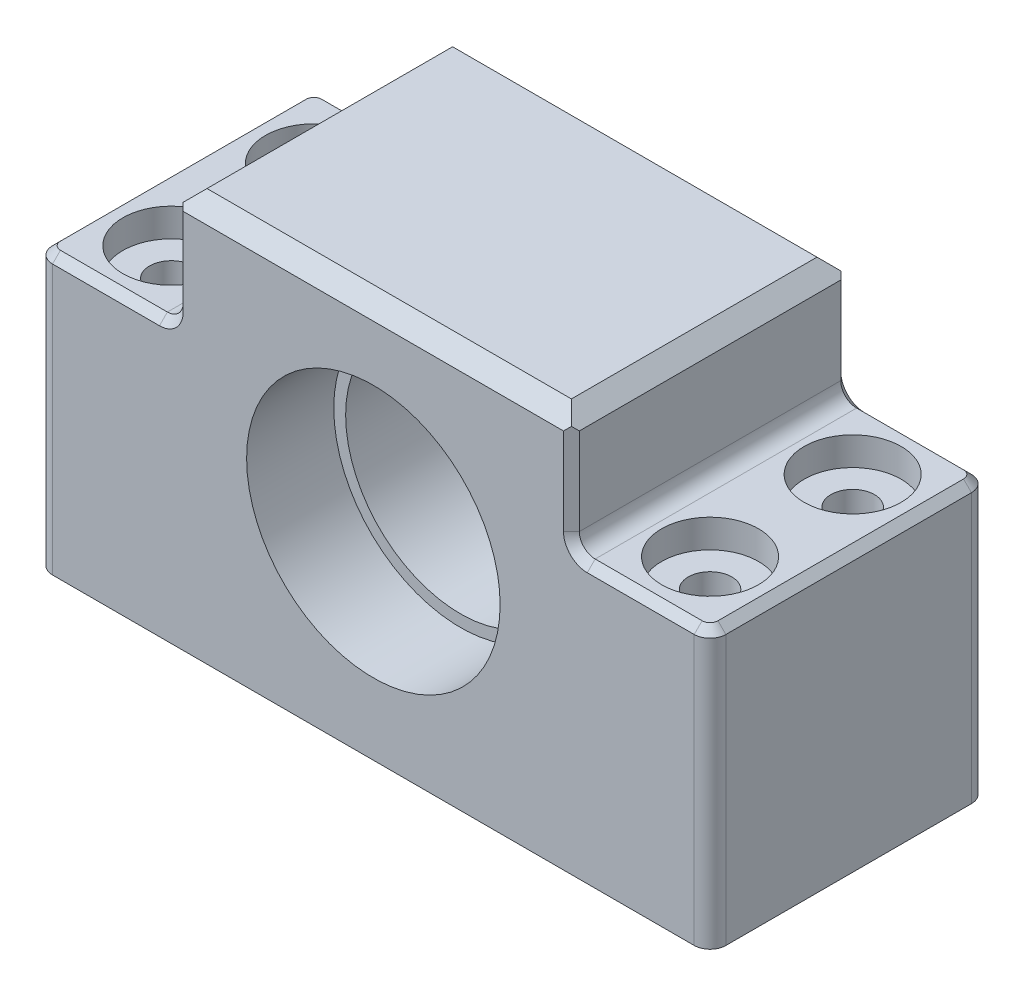
SolidWorks part; units mm, degrees
ref_plane "Front Plane" through (0, 0, 0) normal (0, 0, 1) x (1, 0, 0)
ref_plane "Top Plane" through (0, 0, 0) normal (0, 1, 0) x (1, 0, 0)
ref_plane "Right Plane" through (0, 0, 0) normal (1, 0, 0) x (0, 0, -1)
sketch "Sketch1" plane through (0, 0, 0) normal (0, 0, 1) x (1, 0, 0)
  line L0 (-25, -30) -> (-42.5, -30)
  line L1 (25, -30) -> (-25, -30)
  line L2 (25, -30) -> (25, 20) construction
  line L3 (25, 20) -> (-25, 20)
  line L4 (-25, -30) -> (-25, 20) construction
  line L5 (25, -30) -> (-25, 20) construction
  line L6 (25, 20) -> (-25, -30) construction
  line L7 (-42.5, -30) -> (-42.5, 5)
  line L8 (-42.5, 5) -> (-25, 5)
  line L9 (-25, 5) -> (-25, 20)
  line L10 (0, -55) -> (0, 55) construction
  line L11 (42.5, 5) -> (25, 5)
  line L12 (42.5, -30) -> (42.5, 5)
  line L13 (25, -30) -> (42.5, -30)
  line L14 (25, 5) -> (25, 20)
  circle A1 centre (0, -5) radius 16
  point P0 (0, -5)
  dimension "D1" = 25
  dimension "D3" = 32
  dimension "D2" = 50
  dimension "D4" = 85
  dimension "D5" = 35
  dimension "D6" = 50
extrude "Boss-Extrude1" add sketch "Sketch1" along normal mid plane 35
sketch "Sketch2" plane through (0, 0, 0) normal (0, 0, 1) x (1, 0, 0)
  circle A3 centre (0, -5) radius 16 construction
  circle A4 centre (0, -5) radius 16
  circle A5 centre (0, -5) radius 14.5
  dimension "D1" = 1.5
extrude "Boss-Extrude2" add sketch "Sketch2" along normal mid plane 13
sketch "Sketch3" plane through (0, 5, 0) normal (0, 1, 0) x (1, 0, 0)
  line L0 (34, 0) -> (-34, 0) construction
  line L1 (-34, -9) -> (-34, 9) construction
  line L4 (0, -55) -> (0, 55) construction
  line L5 (34, -9) -> (34, 9) construction
  circle A0 centre (-34, 9) radius 2.6
  circle A1 centre (-34, -9) radius 2.6
  circle A2 centre (34, 9) radius 2.6
  circle A3 centre (34, -9) radius 2.6
  point P8 (0, 0)
  dimension "D1" = 5.2
  dimension "D2" = 34
  dimension "D3" = 9
extrude "Cut-Extrude1" cut sketch "Sketch3" against normal through all
hole_wizard "CBORE for M5 Hex Head Bolt1" positions "3DSketch1" profile "Sketch4" counterbore size "M5" standard "ANSI Metric" end condition through all
sketch3d "3DSketch1"
  line L0 (-34, -30, -9) -> (-34, 5, -9) construction
  line L1 (-34, -30, 9) -> (-34, 5, 9) construction
  line L2 (34, -30, 9) -> (34, 5, 9) construction
  line L3 (34, -30, -9) -> (34, 5, -9) construction
  point P0 (-34, 5, -9)
  point P4 (-34, 5, 9)
  point P8 (34, 5, 9)
  point P12 (34, 5, -9)
sketch "Sketch4" plane through (-34, 5, -9) normal (1, 0, 0) x (0, 0, 1)
  line L0 (0, 0) -> (0, 35)
  line L1 (0, 35) -> (2.75, 35)
  line L3 (2.75, 35) -> (2.75, 3.58)
  line L4 (2.75, 3.58) -> (6.12, 3.58)
  line L5 (6.12, 3.58) -> (6.12, 0)
  line L7 (6.12, 0) -> (0, 0)
  line L11 (0, -6.35) -> (0, 107.95) construction
  dimension "Thru Hole Dia." = 5.5
  dimension "Thru Hole Depth" = 35
  dimension "C'Bore Dia." = 12.24
  dimension "C'Bore Depth" = 3.58
chamfer "Chamfer1" distance 2 angle 45 4 edges at (0, 20, 17.5) (25, 20, 0) (0, 20, -17.5) (-25, 20, 0)
fillet "Fillet1" radius 2 6 edges at (-25, 5, 0) (-42.5, -12.5, 17.5) (-42.5, -12.5, -17.5) (25, 5, 0) (42.5, -12.5, 17.5) (42.5, -12.5, -17.5)
chamfer "Chamfer2" distance 1 angle 45 18 edges at (25, 12.5, -17.5) (25.5858, 5.5858, -17.5) (33.75, 5, -17.5) (41.9142, 5, -16.9142) (42.5, 5, 0) (41.9142, 5, 16.9142) (33.75, 5, 17.5) (25.5858, 5.5858, 17.5) (25, 12.5, 17.5) (-25, 12.5, -17.5) (-25.5858, 5.5858, -17.5) (-33.75, 5, -17.5) (-25, 12.5, 17.5) (-41.9142, 5, -16.9142) (-25.5858, 5.5858, 17.5) (-42.5, 5, 0) (-41.9142, 5, 16.9142) (-33.75, 5, 17.5)
